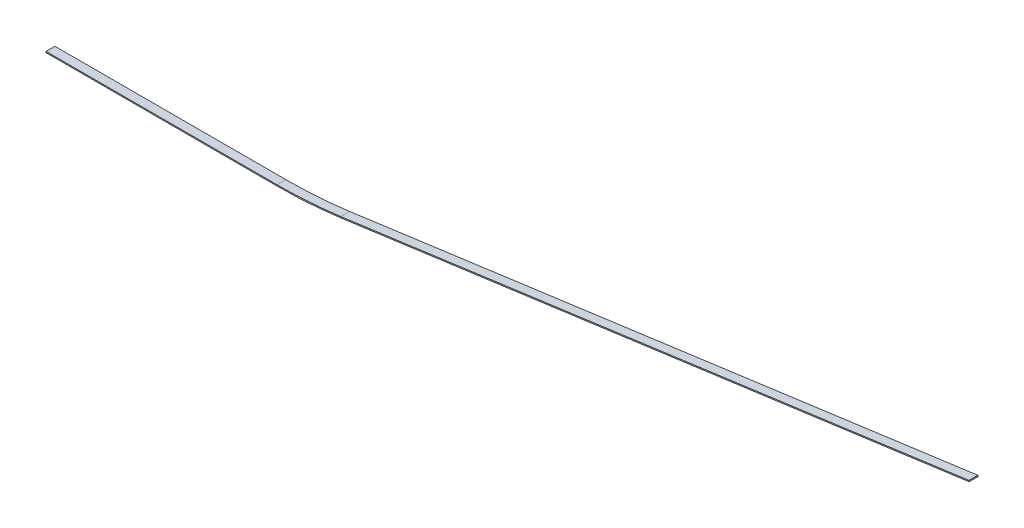
SolidWorks part; units mm, degrees
ref_plane "Front Plane" through (0, 0, 0) normal (0, 0, 1) x (1, 0, 0)
ref_plane "Top Plane" through (0, 0, 0) normal (0, 1, 0) x (1, 0, 0)
ref_plane "Right Plane" through (0, 0, 0) normal (1, 0, 0) x (0, 0, -1)
sketch "Sketch2" plane through (0, 0, 0) normal (0, 0, 1) x (1, 0, 0)
  line L0 (5501.6922, 3000.8922) -> (5501.6922, 3002.1114)
  line L1 (5501.6922, 3000.8922) -> (5749.8028, 3000.8922)
  line L2 (5501.6922, 3002.1114) -> (5749.8028, 3002.1114)
  line L3 (5818.4158, 3005.5471) -> (6493.3157, 3097.5453)
  line L4 (5818.2511, 3006.7551) -> (6493.146, 3098.7527)
  line L5 (6493.3157, 3097.5453) -> (6493.146, 3098.7527)
  arc A0 (5749.8028, 3000.8922) -> (5818.4158, 3005.5471) centre (5749.8028, 3508.8922) ccw
  arc A1 (5749.8028, 3002.1114) -> (5818.2511, 3006.7551) centre (5749.8028, 3508.8922) ccw
extrude "Boss-Extrude1" add sketch "Sketch2" along normal blind 9.525
